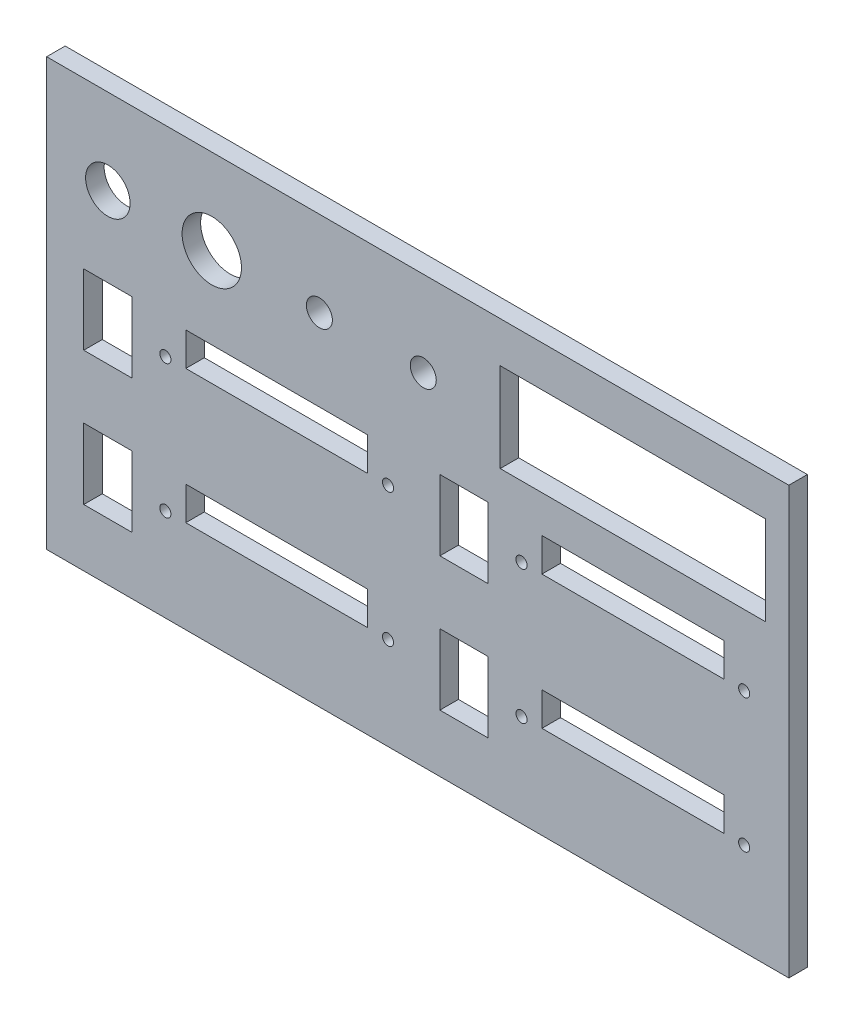
SolidWorks part; units mm, degrees
ref_plane "Front Plane" through (0, 0, 0) normal (0, 0, 1) x (1, 0, 0)
ref_plane "Top Plane" through (0, 0, 0) normal (0, 1, 0) x (1, 0, 0)
ref_plane "Right Plane" through (0, 0, 0) normal (1, 0, 0) x (0, 0, -1)
sketch "Sketch1" plane through (0, 0, 0) normal (0, 0, 1) x (1, 0, 0)
  line L0 (-100, -32.5) -> (100, -32.5) construction
  line L1 (-100, -57.5) -> (100, -57.5)
  line L2 (-100, -57.5) -> (-100, 57.5)
  line L3 (-100, 57.5) -> (100, 57.5)
  line L4 (100, -57.5) -> (100, 57.5)
  line L5 (-100, -57.5) -> (100, 57.5) construction
  line L6 (-100, 57.5) -> (100, -57.5) construction
  line L7 (57.9716, 12.5) -> (57.9716, 64.2324) construction
  line L8 (-62.5, -23.5) -> (-13.5, -23.5)
  line L9 (-62.5, -23.5) -> (-62.5, -32.5)
  line L10 (-62.5, -32.5) -> (-13.5, -32.5)
  line L11 (-13.5, -23.5) -> (-13.5, -32.5)
  line L12 (-90, -42) -> (-77, -42)
  line L13 (-90, -42) -> (-90, -23)
  line L14 (-90, -23) -> (-77, -23)
  line L15 (-77, -42) -> (-77, -23)
  line L16 (-90, -42) -> (-77, -23) construction
  line L17 (-90, -23) -> (-77, -42) construction
  line L18 (-83.5, -32.5) -> (-83.5, 34.5) construction
  line L19 (82.4716, -23.5) -> (82.4716, -32.5)
  line L20 (33.4716, -23.5) -> (82.4716, -23.5)
  line L21 (33.4716, -32.5) -> (82.4716, -32.5)
  line L22 (33.4716, -23.5) -> (33.4716, -32.5)
  line L23 (5.9716, -23) -> (18.9716, -23)
  line L24 (18.9716, -42) -> (18.9716, -23)
  line L25 (5.9716, -42) -> (18.9716, -42)
  line L26 (5.9716, -42) -> (5.9716, -23)
  line L27 (-124.2466, 34.5) -> (151.702, 34.5) construction
  line L28 (82.4716, 12.5) -> (82.4716, 3.5)
  line L29 (33.4716, 12.5) -> (82.4716, 12.5)
  line L30 (33.4716, 3.5) -> (82.4716, 3.5)
  line L31 (33.4716, 12.5) -> (33.4716, 3.5)
  line L32 (5.9716, 13) -> (18.9716, 13)
  line L33 (18.9716, -6) -> (18.9716, 13)
  line L34 (5.9716, -6) -> (18.9716, -6)
  line L35 (5.9716, -6) -> (5.9716, 13)
  line L36 (-13.5, 12.5) -> (-13.5, 3.5)
  line L37 (-62.5, 12.5) -> (-13.5, 12.5)
  line L38 (-62.5, 3.5) -> (-13.5, 3.5)
  line L39 (-62.5, 12.5) -> (-62.5, 3.5)
  line L40 (-90, 13) -> (-77, 13)
  line L41 (-77, -6) -> (-77, 13)
  line L42 (-90, -6) -> (-77, -6)
  line L43 (-90, -6) -> (-90, 13)
  line L48 (21.5, -32.5) -> (221.5, -32.5) construction
  line L51 (22.2216, 46.5) -> (93.7216, 46.5)
  line L52 (22.2216, 46.5) -> (22.2216, 22.5)
  line L53 (22.2216, 22.5) -> (93.7216, 22.5)
  line L54 (93.7216, 46.5) -> (93.7216, 22.5)
  line L55 (22.2216, 46.5) -> (93.7216, 22.5) construction
  line L56 (22.2216, 22.5) -> (93.7216, 46.5) construction
  line L57 (-62.5, 22.3557) -> (-62.5, 13.3557) [skipped]
  line L58 (-62.5, 13.3557) -> (-13.5, 13.3557) [skipped]
  line L59 (-90, 3.8557) -> (-90, 22.8557) [skipped]
  line L60 (-90, 22.8557) -> (-77, 22.8557) [skipped]
  line L61 (-77, 3.8557) -> (-77, 22.8557) [skipped]
  line L62 (-90, 3.8557) -> (-77, 22.8557) construction
  line L63 (-90, 22.8557) -> (-77, 3.8557) construction
  line L64 (-90, 3.8557) -> (-77, 3.8557) [skipped]
  line L65 (-62.5, 22.3557) -> (-13.5, 22.3557) [skipped]
  line L66 (-13.5, 22.3557) -> (-13.5, 13.3557) [skipped]
  line L72 (31.5, -23) -> (44.5, -23) [skipped]
  line L73 (31.5, -54.5) -> (31.5, -45) [skipped]
  line L74 (17.2245, -62.8642) -> (23.7245, -53.3642) construction
  line L75 (35.3755, -28.6642) -> (41.8755, -38.1642) construction
  line L76 (44.5, -54.5) -> (44.5, -45) [skipped]
  line L77 (31.5, -42) -> (44.5, -42) [skipped]
  line L78 (59, -23.5) -> (59, -32.5) [skipped]
  line L79 (54, -23.5) -> (103, -23.5) [skipped]
  line L80 (108, -23.5) -> (108, -32.5) [skipped]
  line L81 (59, -32.5) -> (108, -32.5) [skipped]
  circle A0 centre (-68, -32.5) radius 1.5
  circle A1 centre (-8, -32.5) radius 1.5
  circle A2 centre (87.9716, -32.5) radius 1.5
  circle A3 centre (27.9716, -32.5) radius 1.5
  circle A4 centre (87.9716, 3.5) radius 1.5
  circle A5 centre (27.9716, 3.5) radius 1.5
  circle A6 centre (-8, 3.5) radius 1.5
  circle A7 centre (-68, 3.5) radius 1.5
  circle A8 centre (-83.5, 34.5) radius 6
  circle A9 centre (-68, 13.3557) radius 1.5 [skipped]
  circle A10 centre (-8, 13.3557) radius 1.5 [skipped]
  circle A11 centre (-55.5, 34.5) radius 8
  circle A12 centre (1.5, 34.5) radius 3.5
  arc A13 (52, -32.5) -> (55, -32.5) centre (53.5, -32.5) ccw [skipped]
  circle A14 centre (113.5, -32.5) radius 1.5 [skipped]
  circle A15 centre (-26.5, 34.5) radius 3.5
  point P0 (0, 0)
  point P16 (-38, -32.5)
  point P17 (-83.5, -32.5)
  point P22 (-83.5, 13.3557)
  point P33 (38, -32.5)
  point P59 (38, 13.3557)
  point P69 (57.9716, 34.5)
  dimension "D1" = 3
  dimension "D2" = 3
  dimension "D16" = 12
  dimension "D23" = 16
  dimension "D26" = 7
  dimension "D3" = 60
  dimension "D4" = 200
  dimension "D5" = 115
  dimension "D6" = 49
  dimension "D7" = 9
  dimension "D8" = 30
  dimension "D9" = 9
  dimension "D10" = 13
  dimension "D11" = 19
  dimension "D12" = 15.5
  dimension "D13" = 10
  dimension "D17" = 71.5
  dimension "D18" = 24
  dimension "D19" = 25
  dimension "D22" = 28
  dimension "D24" = 85
  dimension "D25" = 92
  dimension "D27" = 57
  dimension "D28" = 61
  dimension "D29" = 105.9716
  dimension "D14" = 2
  dimension "D15" = 2
  dimension "D20" = 2
  dimension "D21" = 2
extrude "Boss-Extrude1" add sketch "Sketch1" along normal blind 5
